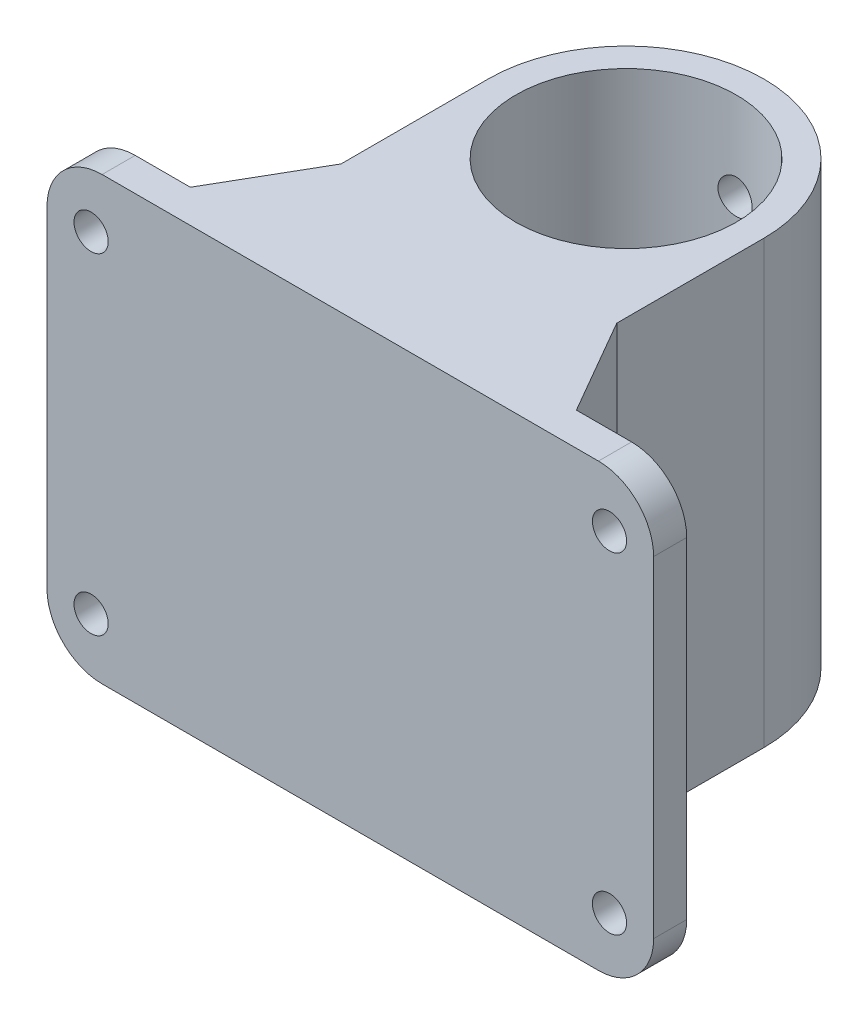
SolidWorks part; units mm, degrees
material "6061 合金"
ref_plane "前视基准面" through (0, 0, 0) normal (0, 0, 1) x (1, 0, 0)
ref_plane "上视基准面" through (0, 0, 0) normal (0, 1, 0) x (1, 0, 0)
ref_plane "右视基准面" through (0, 0, 0) normal (1, 0, 0) x (0, 0, -1)
sketch "草图1" plane through (0, 0, 0) normal (0, 1, 0) x (1, 0, 0)
  line L2 (-12.5, -25) -> (12.5, -25)
  line L3 (-12.5, -25) -> (-12.5, 0)
  line L5 (12.5, -25) -> (12.5, 0)
  arc A0 (12.5, 0) -> (-12.5, 0) centre (0, 0) ccw
  circle A1 centre (0, 0) radius 10
  point P3 (0, -12.5)
  dimension "D1" = 25
  dimension "D3" = 20
extrude "凸台-拉伸1" add sketch "草图1" along normal mid plane 40
sketch "草图7" plane through (0, 0, 0) normal (0, 0, 1) x (1, 0, 0)
  line L0 (0, 0) -> (9.3494, 0) construction
  line L1 (0, -12) -> (0, 12) construction
  line L2 (0, 0) -> (-12.5, 0) construction
  line L3 (-12.5, 20) -> (-12.5, -20) construction
  circle A0 centre (0, -12) radius 1.55
  circle A1 centre (0, 12) radius 1.55
  dimension "D1" = 12
  dimension "D2" = 3.1
extrude "切除-拉伸2" cut sketch "草图7" against normal through all
hole_wizard "M3 螺纹孔1" [suppressed] positions "3D草图1" profile "草图8" tap size "M3" standard "GB"
sketch3d "3D草图1"
  point P0 (-7, -8, 25)
  point P7 (7, -8, 25)
  point P9 (7, 8, 25)
  point P11 (-7, 8, 25)
sketch "草图8" plane through (-7, -8, 25) normal (1, 0, 0) x (0, -1, 0)
  line L0 (0, 0) -> (0, 10.2511)
  line L1 (0, 10.2511) -> (1.25, 9.5)
  line L2 (1.25, 9.5) -> (1.25, 0)
  line L5 (1.25, 0) -> (0, 0)
  line L10 (0, 10.2511) -> (-1.25, 9.5) construction
  line L11 (0, -6.35) -> (0, 107.95) construction
  dimension "螺纹孔钻头直径" = 2.5
  dimension "螺纹孔钻头深度" = 9.5
  dimension "导头角度" = 118
cosmetic thread "孔螺蚊线1" [suppressed] parameters "D1"=8, "D2"=3
cosmetic thread "孔螺蚊线2" [suppressed] parameters "D1"=8, "D2"=3
cosmetic thread "孔螺蚊线3" [suppressed] parameters "D1"=8, "D2"=3
cosmetic thread "孔螺蚊线4" [suppressed] parameters "D1"=8, "D2"=3
sketch "草图9" plane through (12.5, 0, 0) normal (1, 0, 0) x (0, 0, -1)
  line L0 (-25, 20) -> (0, 20) construction
  line L1 (-25, -20) -> (-22, -20)
  line L2 (-25, -20) -> (-25, 20)
  line L3 (-25, 20) -> (-22, 20)
  line L4 (-22, -20) -> (-22, 20)
  dimension "D1" = 3
extrude "凸台-拉伸2" add sketch "草图9" along normal blind 15
sketch "草图10" plane through (0, 0, 22) normal (0, 0, -1) x (-1, 0, 0)
  line L0 (-12.5, 0) -> (-27.5, 0) construction
  line L3 (-12.5, -20) -> (-12.5, 20) construction
  line L4 (-27.5, -20) -> (-27.5, 20) construction
  line L5 (-27.5, 20) -> (-12.5, 20) construction
  circle A0 centre (-23.5, 15) radius 1.55
  circle A1 centre (-23.5, -15) radius 1.55
  dimension "D1" = 4
  dimension "D2" = 3.1
  dimension "D3" = 5
extrude "切除-拉伸3" cut sketch "草图10" against normal through all
ref_plane "基准面1" through (0, 0, 0) normal (1, 0, 0) x (0, 0, -1)
mirror "镜向6" about plane through (0, 0, 0) normal (1, 0, 0) of "切除-拉伸3", "凸台-拉伸2"
chamfer "倒角1" distance 5 angle 60 2 edges at (12.5, 0, 22) (-12.5, 0, 22)
fillet "圆角1" radius 5 4 edges at (-27.5, 20, 23.5) (-27.5, -20, 23.5) (27.5, 20, 23.5) (27.5, -20, 23.5)
